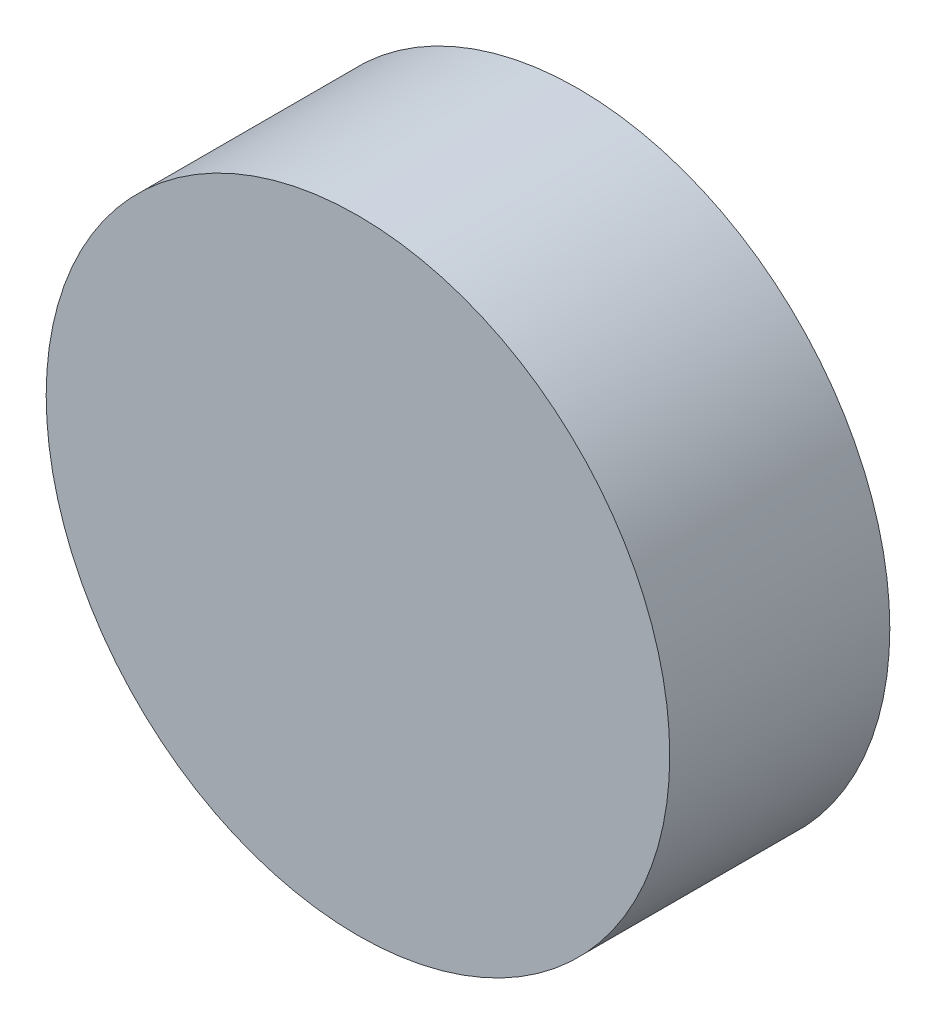
SolidWorks part; units mm, degrees
material "普通碳钢"
ref_plane "前视基准面" through (0, 0, 0) normal (0, 0, 1) x (1, 0, 0)
ref_plane "上视基准面" through (0, 0, 0) normal (0, 1, 0) x (1, 0, 0)
ref_plane "右视基准面" through (0, 0, 0) normal (1, 0, 0) x (0, 0, -1)
sketch "草图1" plane through (0, 0, 0) normal (0, 0, 1) x (1, 0, 0)
  circle A0 centre (0, 0) radius 0.0425
extrude "凸台-拉伸1" add sketch "草图1" along normal blind 0.03
